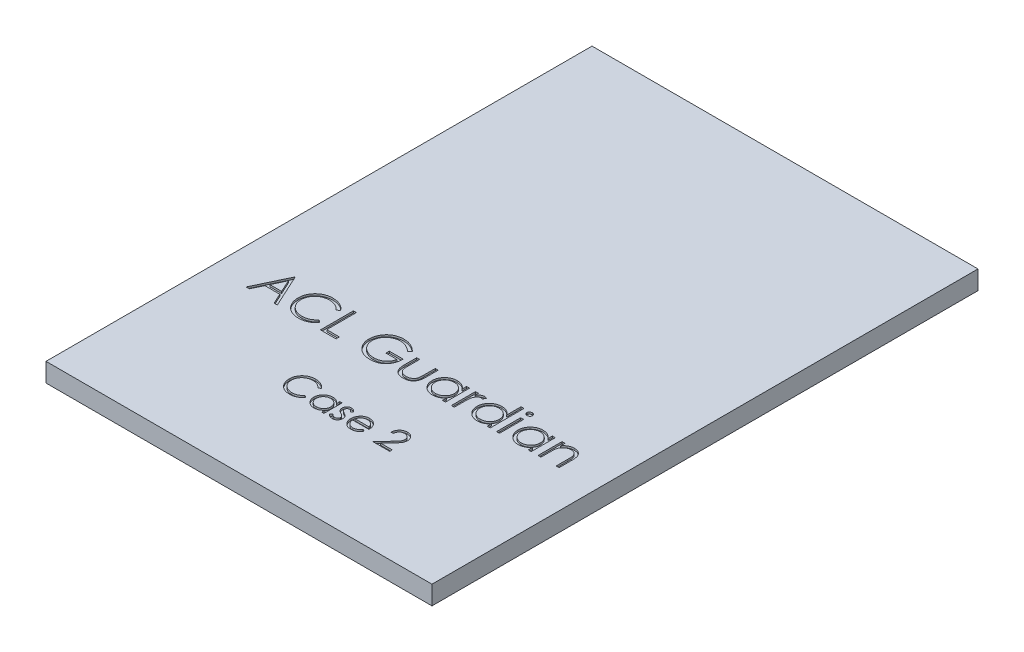
SolidWorks part; units mm, degrees
ref_plane "Front Plane" through (0, 0, 0) normal (0, 0, 1) x (1, 0, 0)
ref_plane "Top Plane" through (0, 0, 0) normal (0, 1, 0) x (1, 0, 0)
ref_plane "Right Plane" through (0, 0, 0) normal (1, 0, 0) x (0, 0, -1)
sketch "Sketch1" plane through (0, 0, 0) normal (0, 0, 1) x (1, 0, 0)
  line L1 (0, 0) -> (41, 0)
  line L2 (0, 0) -> (0, -2)
  line L3 (0, -2) -> (41, -2)
  line L4 (41, 0) -> (41, -2)
  dimension "D1" = 41
  dimension "D2" = 2
extrude "Boss-Extrude1" add sketch "Sketch1" along normal blind 58
sketch "Sketch2" plane through (0, 0, 0) normal (0, 1, 0) x (1, 0, 0)
  line L0 (0, -40.5333) -> (41, -40.5333) construction
  line L1 (0, -58) -> (0, 0) construction
  line L2 (41, -58) -> (41, 0) construction
  line L3 (0, -48.0259) -> (41, -48.0259) construction
  text T0 "ACL Guardian"
  text T1 "Case 2" font "Century Gothic" height in points 10
extrude "Cut-Extrude1" cut sketch "Sketch2" against normal blind 0.2
